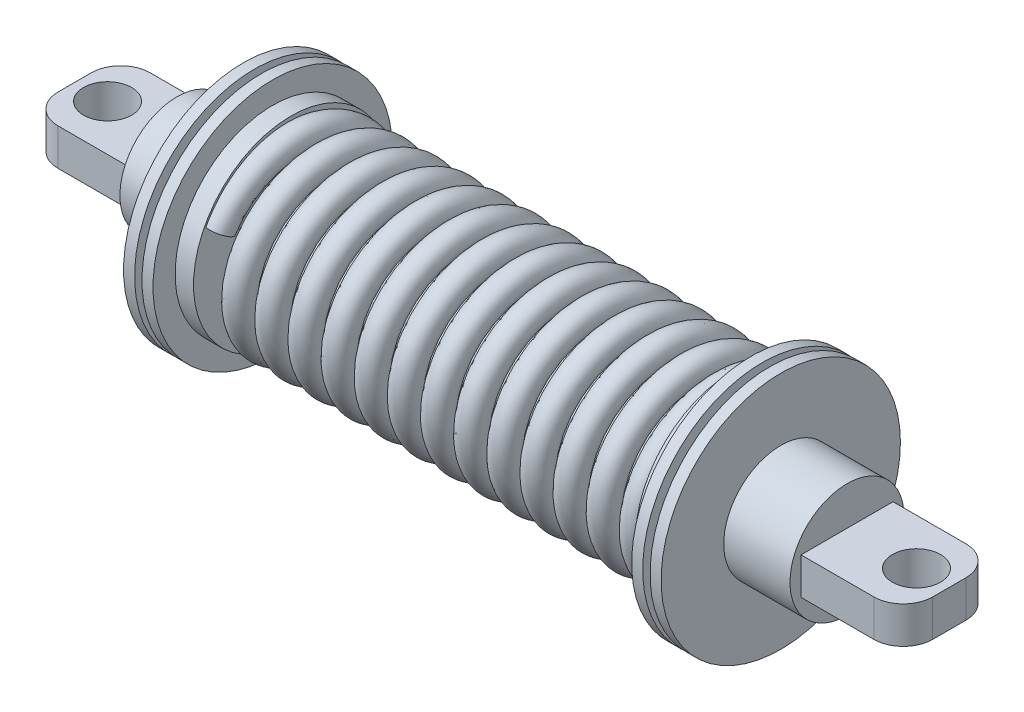
SolidWorks part; units mm, degrees
ref_plane "Front Plane" through (0, 0, 0) normal (0, 0, 1) x (1, 0, 0)
ref_plane "Top Plane" through (0, 0, 0) normal (0, 1, 0) x (1, 0, 0)
ref_plane "Right Plane" through (0, 0, 0) normal (1, 0, 0) x (0, 0, -1)
sketch "Sketch1" plane through (0, 0, 0) normal (0, 0, 1) x (1, 0, 0)
  line L0 (0, 0) -> (0, 19779.6818) construction
  line L5 (0, 0) -> (-19779.6818, 0) construction
  line L6 (-60, 13) -> (60, 13)
  line L7 (60, 13) -> (60, 26.5)
  line L8 (60, 26.5) -> (65, 26.5)
  line L9 (65, 26.5) -> (65, 32.5)
  line L10 (68, 32.5) -> (68, 18.5)
  line L11 (68, 18.5) -> (70, 18.5)
  line L12 (70, 18.5) -> (70, 32.5)
  line L13 (70, 32.5) -> (73, 32.5)
  line L14 (73, 32.5) -> (73, 15.5)
  line L15 (73, 15.5) -> (91, 15.5)
  line L16 (91, 15.5) -> (91, 0)
  line L17 (91, 0) -> (-91, 0)
  line L18 (65, 32.5) -> (68, 32.5)
  line L19 (-91, 15.5) -> (-91, 0)
  line L20 (-65, 32.5) -> (-68, 32.5)
  line L21 (-73, 15.5) -> (-91, 15.5)
  line L22 (-73, 32.5) -> (-73, 15.5)
  line L23 (-70, 32.5) -> (-73, 32.5)
  line L24 (-70, 18.5) -> (-70, 32.5)
  line L25 (-68, 18.5) -> (-70, 18.5)
  line L26 (-68, 32.5) -> (-68, 18.5)
  line L27 (-65, 26.5) -> (-65, 32.5)
  line L28 (-60, 26.5) -> (-65, 26.5)
  line L29 (-60, 13) -> (-60, 26.5)
  point P21 (0, 0)
  point P22 (0, 13)
  dimension "D1" = 3
  dimension "D2" = 3
  dimension "D3" = 2
  dimension "D4" = 5
  dimension "D5" = 17
  dimension "D6" = 6
  dimension "D7" = 13
  dimension "D8" = 15.5
  dimension "D9" = 18
  dimension "D10" = 14
  dimension "D11" = 60
revolve "Revolve1" add sketch "Sketch1" angle 360 about L5
sketch "Sketch2" plane through (0, 0, 0) normal (0, 1, 0) x (1, 0, 0)
  line L0 (91, -15.5) -> (91, 15.5) construction
  line L1 (91, -12.5) -> (110.774, -12.5)
  line L2 (91, -12.5) -> (91, 12.5)
  line L3 (91, 12.5) -> (110.774, 12.5)
  line L4 (118.774, -4.5) -> (118.774, 4.5)
  line L6 (73, -15.5) -> (91, -15.5) construction
  line L7 (91, 15.5) -> (73, 15.5) construction
  circle A0 centre (109.8511, 0) radius 6.5337
  arc A1 (110.774, -12.5) -> (118.774, -4.5) centre (110.774, -4.5) ccw
  arc A2 (110.774, 12.5) -> (118.774, 4.5) centre (110.774, 4.5) cw
  point P12 (0, 0)
  point P14 (110.3126, -4.5431)
  point P18 (0, 0)
  dimension "D4" = 8
  dimension "D1" = 3
  dimension "D2" = 3
  dimension "D3" = 12.5
extrude "Boss-Extrude1" add sketch "Sketch2" along normal mid plane 10
mirror "Mirror1" about plane through (0, 0, 0) normal (1, 0, 0) of "Boss-Extrude1"
sketch "Sketch3" plane through (60, 0, 0) normal (-1, 0, 0) x (0, 0, 1)
  circle A0 centre (0, 0) radius 22.5
  dimension "D1" = 45
curve "Helix/Spiral1" pitch 9 height 119.7 turns 13.3
sweep "Sweep1" add path "Helix/Spiral1" parameters "D3"=7
